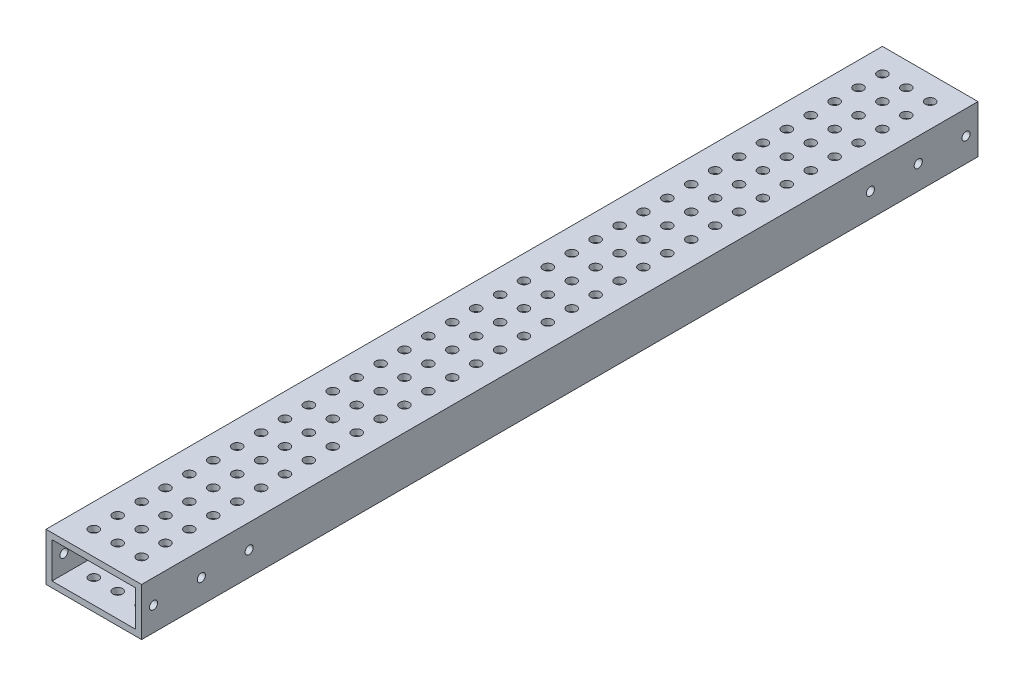
SolidWorks part; units mm, degrees
ref_plane "Front Plane" through (0, 0, 0) normal (0, 0, 1) x (1, 0, 0)
ref_plane "Top Plane" through (0, 0, 0) normal (0, 1, 0) x (1, 0, 0)
ref_plane "Right Plane" through (0, 0, 0) normal (1, 0, 0) x (0, 0, -1)
sketch "Sketch1" plane through (0, 0, 0) normal (0, 0, 1) x (1, 0, 0)
  line L0 (-22.225, 9.525) -> (22.225, 9.525)
  line L1 (-25.4, 12.7) -> (25.4, 12.7)
  line L2 (-25.4, 12.7) -> (-25.4, -12.7)
  line L3 (-25.4, -12.7) -> (25.4, -12.7)
  line L4 (25.4, 12.7) -> (25.4, -12.7)
  line L5 (22.225, 9.525) -> (22.225, -9.525)
  line L6 (-22.225, -9.525) -> (22.225, -9.525)
  line L7 (-22.225, 9.525) -> (-22.225, -9.525)
  line L8 (-25.4, 12.7) -> (25.4, -12.7) construction
  line L9 (25.4, 12.7) -> (-25.4, -12.7) construction
  point P5 (0, 0)
  dimension "D1" = 50.8
  dimension "D2" = 25.4
  dimension "D3" = 3.175
extrude "Boss-Extrude1" add sketch "Sketch1" along normal mid plane 444.5
sketch "Sketch2" plane through (0, 12.7, 0) normal (0, 1, 0) x (1, 0, 0)
  line L0 (25.4, -222.25) -> (-25.4, -222.25) construction
  line L1 (-25.4, -222.25) -> (-25.4, 222.25) construction
  line L2 (-12.7, -209.55) -> (0, -209.55) construction
  line L3 (0, -209.55) -> (12.7, -209.55) construction
  circle A0 centre (0, -209.55) radius 2.5527
  circle A1 centre (12.7, -209.55) radius 2.5527
  circle A2 centre (-12.7, -209.55) radius 2.5527
  circle A3 centre (-12.7, -196.85) radius 2.5527
  circle A4 centre (0, -196.85) radius 2.5527
  circle A5 centre (12.7, -196.85) radius 2.5527
  circle A6 centre (-12.7, -184.15) radius 2.5527
  circle A7 centre (0, -184.15) radius 2.5527
  circle A8 centre (12.7, -184.15) radius 2.5527
  circle A9 centre (-12.7, -171.45) radius 2.5527
  circle A10 centre (0, -171.45) radius 2.5527
  circle A11 centre (12.7, -171.45) radius 2.5527
  circle A12 centre (-12.7, -158.75) radius 2.5527
  circle A13 centre (0, -158.75) radius 2.5527
  circle A14 centre (12.7, -158.75) radius 2.5527
  circle A15 centre (-12.7, -146.05) radius 2.5527
  circle A16 centre (0, -146.05) radius 2.5527
  circle A17 centre (12.7, -146.05) radius 2.5527
  circle A18 centre (-12.7, -133.35) radius 2.5527
  circle A19 centre (0, -133.35) radius 2.5527
  circle A20 centre (12.7, -133.35) radius 2.5527
  circle A21 centre (-12.7, -120.65) radius 2.5527
  circle A22 centre (0, -120.65) radius 2.5527
  circle A23 centre (12.7, -120.65) radius 2.5527
  circle A24 centre (-12.7, -107.95) radius 2.5527
  circle A25 centre (0, -107.95) radius 2.5527
  circle A26 centre (12.7, -107.95) radius 2.5527
  circle A27 centre (-12.7, -95.25) radius 2.5527
  circle A28 centre (0, -95.25) radius 2.5527
  circle A29 centre (12.7, -95.25) radius 2.5527
  circle A30 centre (-12.7, -82.55) radius 2.5527
  circle A31 centre (0, -82.55) radius 2.5527
  circle A32 centre (12.7, -82.55) radius 2.5527
  circle A33 centre (-12.7, -69.85) radius 2.5527
  circle A34 centre (0, -69.85) radius 2.5527
  circle A35 centre (12.7, -69.85) radius 2.5527
  circle A36 centre (-12.7, -57.15) radius 2.5527
  circle A37 centre (0, -57.15) radius 2.5527
  circle A38 centre (12.7, -57.15) radius 2.5527
  circle A39 centre (-12.7, -44.45) radius 2.5527
  circle A40 centre (0, -44.45) radius 2.5527
  circle A41 centre (12.7, -44.45) radius 2.5527
  circle A42 centre (-12.7, -31.75) radius 2.5527
  circle A43 centre (0, -31.75) radius 2.5527
  circle A44 centre (12.7, -31.75) radius 2.5527
  circle A45 centre (-12.7, -19.05) radius 2.5527
  circle A46 centre (0, -19.05) radius 2.5527
  circle A47 centre (12.7, -19.05) radius 2.5527
  circle A48 centre (-12.7, -6.35) radius 2.5527
  circle A49 centre (0, -6.35) radius 2.5527
  circle A50 centre (12.7, -6.35) radius 2.5527
  circle A51 centre (-12.7, 6.35) radius 2.5527
  circle A52 centre (0, 6.35) radius 2.5527
  circle A53 centre (12.7, 6.35) radius 2.5527
  circle A54 centre (-12.7, 19.05) radius 2.5527
  circle A55 centre (0, 19.05) radius 2.5527
  circle A56 centre (12.7, 19.05) radius 2.5527
  circle A57 centre (-12.7, 31.75) radius 2.5527
  circle A58 centre (0, 31.75) radius 2.5527
  circle A59 centre (12.7, 31.75) radius 2.5527
  circle A60 centre (-12.7, 44.45) radius 2.5527
  circle A61 centre (0, 44.45) radius 2.5527
  circle A62 centre (12.7, 44.45) radius 2.5527
  circle A63 centre (-12.7, 57.15) radius 2.5527
  circle A64 centre (0, 57.15) radius 2.5527
  circle A65 centre (12.7, 57.15) radius 2.5527
  circle A66 centre (-12.7, 69.85) radius 2.5527
  circle A67 centre (0, 69.85) radius 2.5527
  circle A68 centre (12.7, 69.85) radius 2.5527
  circle A69 centre (-12.7, 82.55) radius 2.5527
  circle A70 centre (0, 82.55) radius 2.5527
  circle A71 centre (12.7, 82.55) radius 2.5527
  circle A72 centre (-12.7, 95.25) radius 2.5527
  circle A73 centre (0, 95.25) radius 2.5527
  circle A74 centre (12.7, 95.25) radius 2.5527
  circle A75 centre (-12.7, 107.95) radius 2.5527
  circle A76 centre (0, 107.95) radius 2.5527
  circle A77 centre (12.7, 107.95) radius 2.5527
  circle A78 centre (-12.7, 120.65) radius 2.5527
  circle A79 centre (0, 120.65) radius 2.5527
  circle A80 centre (12.7, 120.65) radius 2.5527
  circle A81 centre (-12.7, 133.35) radius 2.5527
  circle A82 centre (0, 133.35) radius 2.5527
  circle A83 centre (12.7, 133.35) radius 2.5527
  circle A84 centre (-12.7, 146.05) radius 2.5527
  circle A85 centre (0, 146.05) radius 2.5527
  circle A86 centre (12.7, 146.05) radius 2.5527
  circle A87 centre (-12.7, 158.75) radius 2.5527
  circle A88 centre (0, 158.75) radius 2.5527
  circle A89 centre (12.7, 158.75) radius 2.5527
  circle A90 centre (-12.7, 171.45) radius 2.5527
  circle A91 centre (0, 171.45) radius 2.5527
  circle A92 centre (12.7, 171.45) radius 2.5527
  circle A93 centre (-12.7, 184.15) radius 2.5527
  circle A94 centre (0, 184.15) radius 2.5527
  circle A95 centre (12.7, 184.15) radius 2.5527
  circle A96 centre (-12.7, 196.85) radius 2.5527
  circle A97 centre (0, 196.85) radius 2.5527
  circle A98 centre (12.7, 196.85) radius 2.5527
  circle A99 centre (-12.7, 209.55) radius 2.5527
  circle A100 centre (0, 209.55) radius 2.5527
  circle A101 centre (12.7, 209.55) radius 2.5527
  circle A108 centre (-12.7, 234.95) radius 2.5527 [skipped]
  circle A109 centre (0, 234.95) radius 2.5527 [skipped]
  circle A110 centre (12.7, 234.95) radius 2.5527 [skipped]
  circle A111 centre (-12.7, 222.25) radius 2.5527 [skipped]
  circle A112 centre (0, 222.25) radius 2.5527 [skipped]
  circle A113 centre (12.7, 222.25) radius 2.5527 [skipped]
  dimension "D2" = 5.1054
  dimension "D4" = 12.7
  dimension "D1" = 12.7
  dimension "D3" = 25.4
  dimension "D5" = 36
extrude "Cut-Extrude1" cut sketch "Sketch2" against normal through all
sketch "Sketch3" plane through (25.4, 0, 0) normal (1, 0, 0) x (0, 0, -1)
  line L0 (-222.25, -12.7) -> (-222.25, 12.7) construction
  line L1 (-222.25, 12.7) -> (222.25, 12.7) construction
  line L2 (222.25, -12.7) -> (222.25, 12.7) construction
  circle A0 centre (-215.9, 0) radius 2.159
  circle A1 centre (-190.5, 0) radius 2.159
  circle A2 centre (-165.1, 0) radius 2.159
  circle A3 centre (215.9, 0) radius 2.159
  circle A4 centre (190.5, 0) radius 2.159
  circle A5 centre (165.1, 0) radius 2.159
  dimension "D2" = 4.318
  dimension "D9" = 4.318
  dimension "D1" = 6.35
  dimension "D3" = 12.7
  dimension "D4" = 31.75
  dimension "D5" = 12.7
  dimension "D6" = 57.15
  dimension "D7" = 12.7
  dimension "D8" = 6.35
  dimension "D10" = 12.7
  dimension "D11" = 31.75
  dimension "D12" = 57.15
  dimension "D13" = 12.7
  dimension "D14" = 12.7
extrude "Cut-Extrude2" cut sketch "Sketch3" against normal through all
